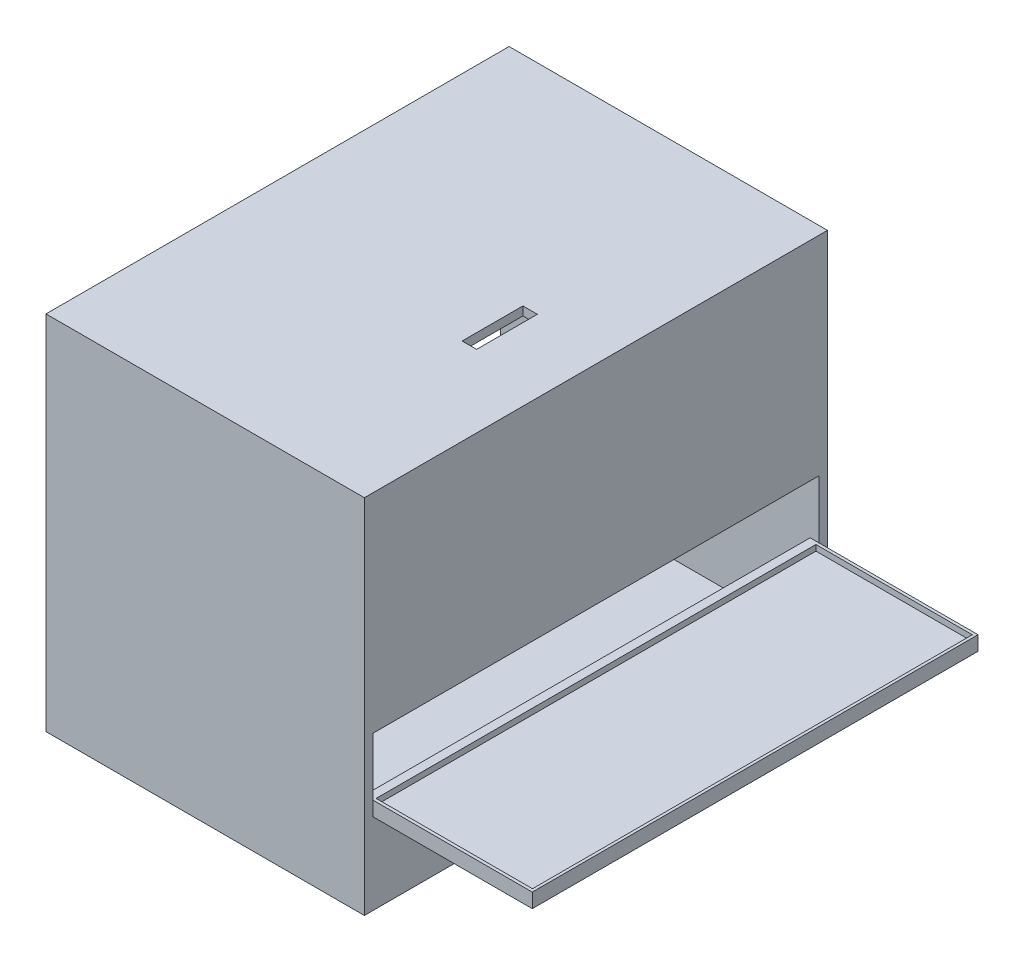
SolidWorks part; units mm, degrees
ref_plane "Plano frontal" through (0, 0, 0) normal (0, 0, 1) x (1, 0, 0)
ref_plane "Plano superior" through (0, 0, 0) normal (0, 1, 0) x (1, 0, 0)
ref_plane "Plano direito" through (0, 0, 0) normal (1, 0, 0) x (0, 0, -1)
sketch "Esboço1" plane through (0, 0, 0) normal (0, 1, 0) x (1, 0, 0)
  line L0 (0, 0) -> (0, 160)
  line L1 (0, 160) -> (110, 160)
  line L2 (110, 160) -> (110, 0)
  line L3 (110, 0) -> (0, 0)
  dimension "D1" = 160
  dimension "D2" = 110
extrude "Ressalto-extrusão1" add sketch "Esboço1" along normal blind 10
sketch "Esboço2" plane through (0, 10, 0) normal (0, 1, 0) x (1, 0, 0)
  line L0 (7.5, 150) -> (7.5, 10)
  line L1 (7.5, 10) -> (102.5, 10)
  line L2 (102.5, 10) -> (102.5, 150)
  line L3 (102.5, 150) -> (7.5, 150)
  line L4 (55, 150) -> (55, 10) construction
  line L5 (55, 160) -> (55, 0) construction
  line L6 (110, 160) -> (0, 160) construction
  line L7 (0, 0) -> (110, 0) construction
  line L8 (7.5, 80) -> (102.5, 80) construction
  line L9 (102.5, 80) -> (0, 80) construction
  line L10 (0, 160) -> (0, 0) construction
  line L11 (0, 80) -> (110, 80) construction
  line L12 (110, 0) -> (110, 160) construction
  dimension "D1" = 140
  dimension "D2" = 95
sketch "Esboço3" plane through (0, 10, 0) normal (0, 1, 0) x (1, 0, 0)
  line L0 (55, 160) -> (55, 0) construction
  line L1 (110, 160) -> (0, 160) construction
  line L2 (0, 0) -> (110, 0) construction
extrude "Corte-extrusão1" cut sketch "Esboço2" against normal blind 2
sketch "Esboço4" plane through (0, 10, 0) normal (0, 1, 0) x (1, 0, 0)
  line L0 (0, 160) -> (0, 150)
  line L1 (0, 160) -> (0, 0) construction
  line L2 (0, 150) -> (102.5, 150)
  line L3 (102.5, 150) -> (102.5, 10)
  line L4 (102.5, 10) -> (0, 10)
  line L5 (0, 10) -> (0, 0)
  line L6 (0, 0) -> (110, 0)
  line L7 (110, 0) -> (110, 160)
  line L8 (110, 160) -> (0, 160)
extrude "Ressalto-extrusão2" add sketch "Esboço4" along normal blind 110
sketch "Esboço6" plane through (0, 0, -150) normal (0, 0, 1) x (1, 0, 0)
  line L1 (102.5, 8) -> (7.5, 8) construction
  line L2 (32.5189, 8) -> (32.5189, 28)
  line L3 (32.5189, 28) -> (57.5225, 28)
  line L4 (57.5225, 28) -> (57.5225, 8)
  line L5 (57.5225, 8) -> (32.5189, 8)
extrude "Corte-extrusão2" cut sketch "Esboço6" against normal blind 10
sketch "Esboço7" plane through (102.5, 0, 0) normal (-1, 0, 0) x (0, 0, 1)
  line L1 (-150, 8) -> (-150, 120) construction
  line L2 (-150, 38.0049) -> (-150, 58.0406)
  line L3 (-150, 58.0406) -> (-10, 58.0406)
  line L4 (-10, 8) -> (-10, 120) construction
  line L5 (-10, 58.0406) -> (-10, 38.0049)
  line L6 (-10, 38.0049) -> (-150, 38.0049)
extrude "Saidaprafiossensores" cut sketch "Esboço7" against normal blind 30
sketch "Esboço8" plane through (110, 0, 0) normal (1, 0, 0) x (0, 0, -1)
  line L0 (10, 38.0049) -> (10, 28.0314)
  line L1 (10, 28.0314) -> (150, 28.0314)
  line L2 (150, 28.0314) -> (150, 38.0049)
  line L3 (150, 38.0049) -> (10, 38.0049) construction
  line L4 (150, 38.0049) -> (10, 38.0049)
extrude "Suporte para sensores" add sketch "Esboço8" along normal blind 55
sketch "Esboço9" plane through (0, 38.0049, 0) normal (0, 1, 0) x (1, 0, 0)
  line L0 (110, 10) -> (165, 10)
  line L1 (165, 10) -> (165, 150)
  line L2 (165, 150) -> (110, 150)
  line L3 (110, 150) -> (110, 10)
extrude "Corte-extrusão4" cut sketch "Esboço9" against normal blind 2
sketch "Esboço5" plane through (0, 120, 0) normal (0, 1, 0) x (1, 0, 0)
  line L0 (0, 160) -> (0, 0)
  line L1 (0, 0) -> (110, 0)
  line L2 (110, 0) -> (110, 160)
  line L3 (110, 160) -> (0, 160)
extrude "Ressalto-extrusão3" add sketch "Esboço5" along normal blind 10
sketch "Esboço11" plane through (0, 130, 0) normal (0, 1, 0) x (1, 0, 0)
  line L0 (80, 63.7636) -> (80, 84.7636)
  line L2 (85, 63.7636) -> (80, 63.7636)
  line L3 (80, 84.7636) -> (85, 84.7636)
  line L4 (85, 84.7636) -> (85, 63.7636)
  dimension "D2" = 5
extrude "Corte-extrusão5" cut sketch "Esboço11" against normal blind 9
sketch "Esboço12" plane through (0, 120, 0) normal (0, -1, 0) x (1, 0, 0)
  line L0 (0, -150) -> (102.5, -150)
  line L1 (102.5, -150) -> (102.5, -10)
  line L2 (102.5, -10) -> (0, -10)
  line L3 (0, -10) -> (0, -150)
extrude "Corte-extrusão6" cut sketch "Esboço12" against normal blind 7
sketch "Esboço13" plane through (0, 0, -150) normal (0, 0, 1) x (1, 0, 0)
  line L0 (7.5, 8) -> (7.5, 10)
  line L1 (7.5, 10) -> (0, 10)
  line L2 (0, 10) -> (0, 127)
  line L3 (0, 127) -> (102.5, 127)
  line L4 (102.5, 127) -> (102.5, 58.0406)
  line L5 (102.5, 58.0406) -> (110, 58.0406)
  line L6 (110, 58.0406) -> (110, 38.0049)
  line L7 (110, 38.0049) -> (102.5, 38.0049)
  line L8 (102.5, 38.0049) -> (102.5, 8)
  line L9 (102.5, 8) -> (7.5, 8)
extrude "Corte-extrusão7" cut sketch "Esboço13" against normal blind 7
sketch "Esboço14" plane through (0, 0, -10) normal (0, 0, -1) x (-1, 0, 0)
  line L0 (-102.5, 127) -> (0, 127)
  line L1 (0, 127) -> (0, 10)
  line L2 (0, 10) -> (-7.5, 10)
  line L3 (-7.5, 10) -> (-7.5, 8)
  line L4 (-7.5, 8) -> (-102.5, 8)
  line L5 (-102.5, 8) -> (-102.5, 38.0049)
  line L6 (-102.5, 38.0049) -> (-110, 38.0049)
  line L7 (-110, 38.0049) -> (-110, 58.0406)
  line L8 (-110, 58.0406) -> (-102.5, 58.0406)
  line L9 (-102.5, 58.0406) -> (-102.5, 127)
extrude "Corte-extrusão8" cut sketch "Esboço14" against normal blind 7
sketch "Esboço15" plane through (0, 0, 0) normal (0, -1, 0) x (1, 0, 0)
  line L0 (110, -160) -> (0, -160)
  line L1 (0, -160) -> (0, 0)
  line L2 (0, 0) -> (110, 0)
  line L3 (110, 0) -> (110, -160)
extrude "Corte-extrusão9" cut sketch "Esboço15" against normal blind 5
sketch "Esboço16" plane through (102.5, 0, 0) normal (-1, 0, 0) x (0, 0, 1)
  line L0 (-157, 127) -> (-157, 8)
  line L1 (-157, 8) -> (-3, 8)
  line L2 (-3, 8) -> (-3, 127)
  line L3 (-3, 127) -> (-157, 127)
extrude "Corte-extrusão10" cut sketch "Esboço16" against normal blind 4.5
sketch "Esboço17" plane through (0, 28.0314, 0) normal (0, -1, 0) x (1, 0, 0)
  line L0 (165, -10) -> (110, -10)
  line L1 (110, -10) -> (110, -150)
  line L2 (110, -150) -> (165, -150)
  line L3 (165, -150) -> (165, -10)
extrude "Corte-extrusão11" cut sketch "Esboço17" against normal blind 5
sketch "Esboço18" plane through (0, 0, -10) normal (0, 0, 1) x (1, 0, 0)
  line L0 (110, 36.0049) -> (110, 33.0314)
  line L1 (110, 33.0314) -> (165, 33.0314)
  line L2 (165, 33.0314) -> (165, 36.0049)
  line L3 (165, 36.0049) -> (110, 36.0049)
extrude "Ressalto-extrusão4" add sketch "Esboço18" along normal blind 7
sketch "Esboço19" plane through (0, 0, -150) normal (0, 0, -1) x (-1, 0, 0)
  line L0 (-165, 36.0049) -> (-165, 33.0314)
  line L1 (-165, 33.0314) -> (-110, 33.0314)
  line L2 (-110, 33.0314) -> (-110, 36.0049)
  line L3 (-110, 36.0049) -> (-165, 36.0049)
extrude "Ressalto-extrusão5" add sketch "Esboço19" along normal blind 7
sketch "Esboço20" plane through (0, 36.0049, 0) normal (0, 1, 0) x (1, 0, 0)
  line L0 (110, 157) -> (110, 156.0071)
  line L1 (110, 157) -> (110, 3) construction
  line L2 (110, 156.0071) -> (164.0309, 156.0071)
  line L3 (164.0309, 156.0071) -> (164.0309, 4.05)
  line L4 (164.0309, 4.05) -> (110, 4.05)
  line L5 (110, 4.05) -> (110, 3)
  line L6 (110, 3) -> (165, 3)
  line L7 (165, 3) -> (165, 157)
  line L8 (165, 157) -> (110, 157)
extrude "Ressalto-extrusão6" add sketch "Esboço20" along normal blind 2
